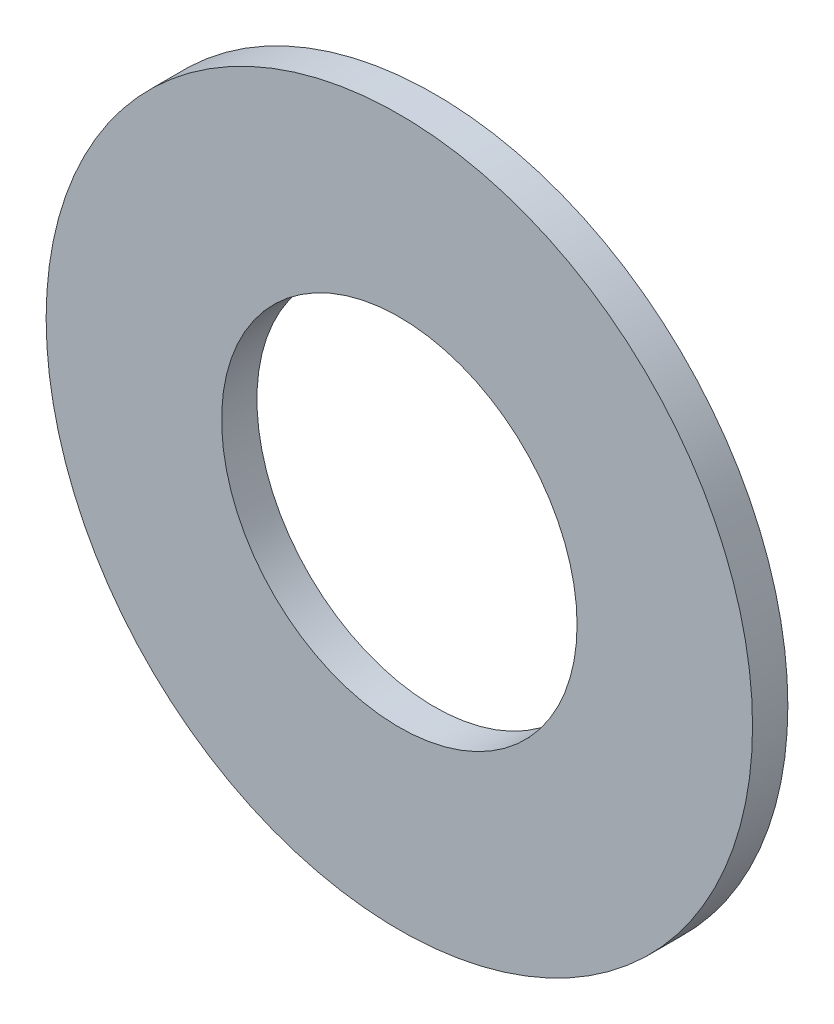
SolidWorks part; units mm, degrees
ref_plane "Front Plane" through (0, 0, 0) normal (0, 0, 1) x (1, 0, 0)
ref_plane "Top Plane" through (0, 0, 0) normal (0, 1, 0) x (1, 0, 0)
ref_plane "Right Plane" through (0, 0, 0) normal (1, 0, 0) x (0, 0, -1)
sketch "Sketch1" plane through (0, 0, 0) normal (0, 0, 1) x (1, 0, 0)
  circle A0 centre (0, 0) radius 15.875
  circle A1 centre (0, 0) radius 7.9883
  dimension "OD" = 31.75
  dimension "ID" = 15.9766
sketch "Sketch2" plane through (0, 0, 0) normal (1, 0, 0) x (0, 0, -1)
  line L0 (-0.7937, 0) -> (0.7937, 0)
  point P4 (0, 0)
  dimension "Thickness" = 1.5875
sketch "Sketch3" plane through (0, 0, 0) normal (0, 0, 1) x (1, 0, 0)
  circle A1 centre (0, 0) radius 7.9883
  circle A2 centre (0, 0) radius 7.9883
  circle A3 centre (0, 0) radius 15.875
  circle A4 centre (0, 0) radius 15.875
  dimension "D1" = 0
  dimension "D2" = 0
extrude "Boss-Extrude1" add sketch "Sketch3" along normal mid plane 1.5875
equation "\"D1@Boss-Extrude1\"=\"Thickness@Sketch2\""
